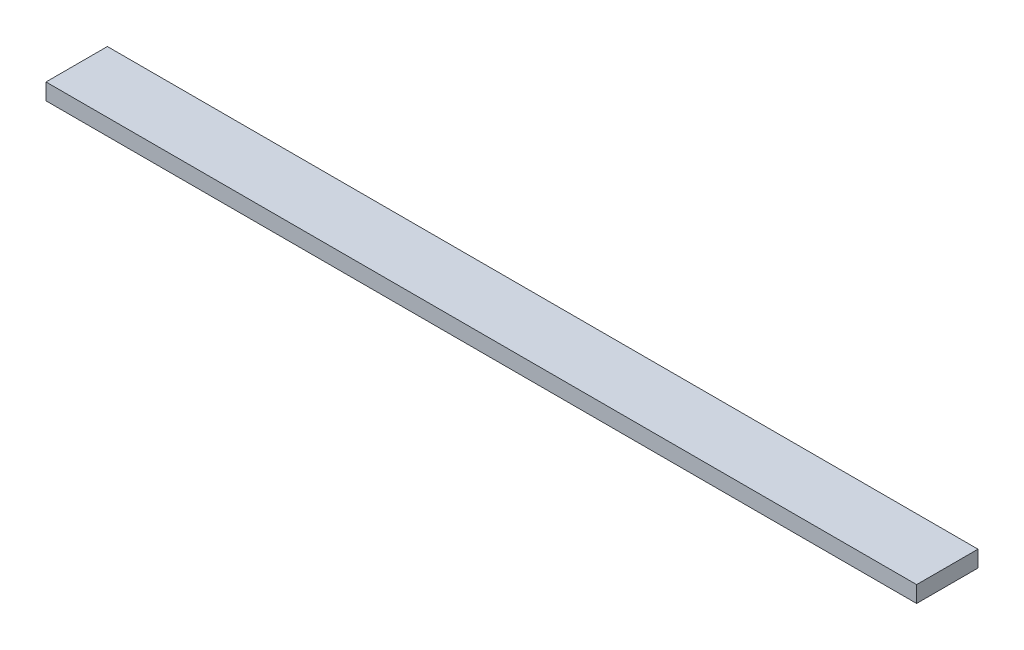
SolidWorks part; units mm, degrees
ref_plane "Front Plane" through (0, 0, 0) normal (0, 0, 1) x (1, 0, 0)
ref_plane "Top Plane" through (0, 0, 0) normal (0, 1, 0) x (1, 0, 0)
ref_plane "Right Plane" through (0, 0, 0) normal (1, 0, 0) x (0, 0, -1)
sketch "Sketch1" plane through (0, 0, 0) normal (0, 1, 0) x (1, 0, 0)
  line L1 (-106.375, -7.5) -> (106.375, -7.5)
  line L2 (-106.375, -7.5) -> (-106.375, 7.5)
  line L3 (-106.375, 7.5) -> (106.375, 7.5)
  line L4 (106.375, -7.5) -> (106.375, 7.5)
  line L5 (-106.375, -7.5) -> (106.375, 7.5) construction
  line L6 (-106.375, 7.5) -> (106.375, -7.5) construction
  point P0 (0, 0)
  dimension "D1" = 212.75
  dimension "D2" = 15
extrude "Boss-Extrude1" add sketch "Sketch1" along normal blind 4
equation "\"D1@Sketch1\"=(851mm/4)"
